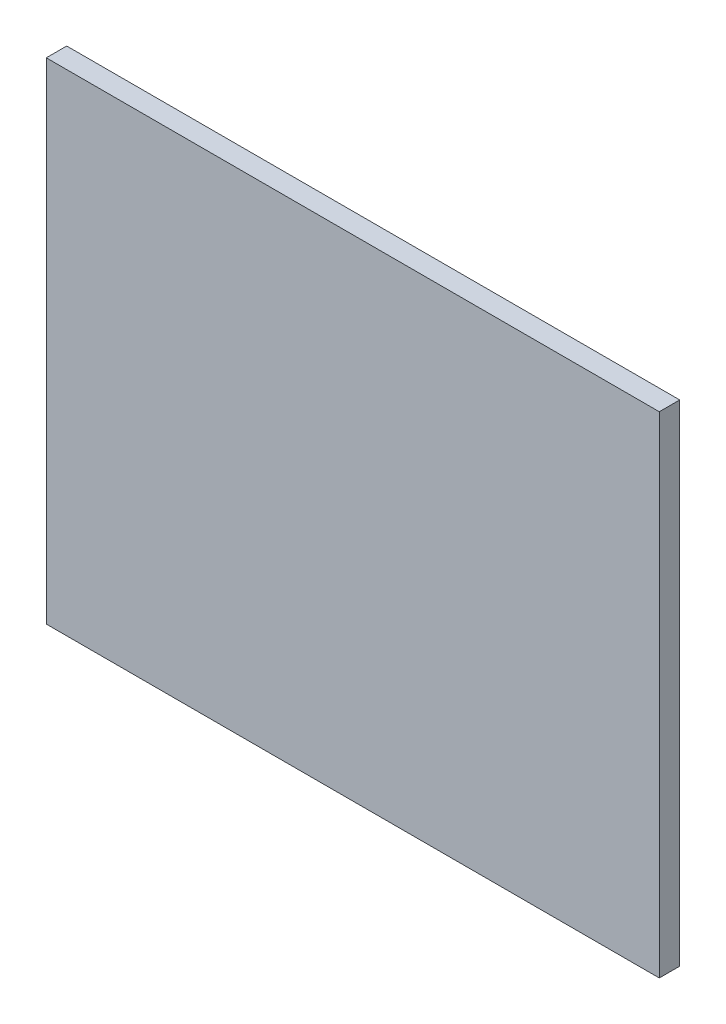
SolidWorks part; units mm, degrees
ref_plane "Front Plane" through (0, 0, 0) normal (0, 0, 1) x (1, 0, 0)
ref_plane "Top Plane" through (0, 0, 0) normal (0, 1, 0) x (1, 0, 0)
ref_plane "Right Plane" through (0, 0, 0) normal (1, 0, 0) x (0, 0, -1)
sketch "Sketch1" plane through (0, 0, 0) normal (0, 0, 1) x (1, 0, 0)
  line L1 (-168.5483, -132.9715) -> (212.4517, -132.9715)
  line L2 (-168.5483, -132.9715) -> (-168.5483, 171.8285)
  line L3 (-168.5483, 171.8285) -> (212.4517, 171.8285)
  line L4 (212.4517, -132.9715) -> (212.4517, 171.8285)
  dimension "D1" = 381
  dimension "D2" = 304.8
extrude "Boss-Extrude1" add sketch "Sketch1" along normal blind 12.7
